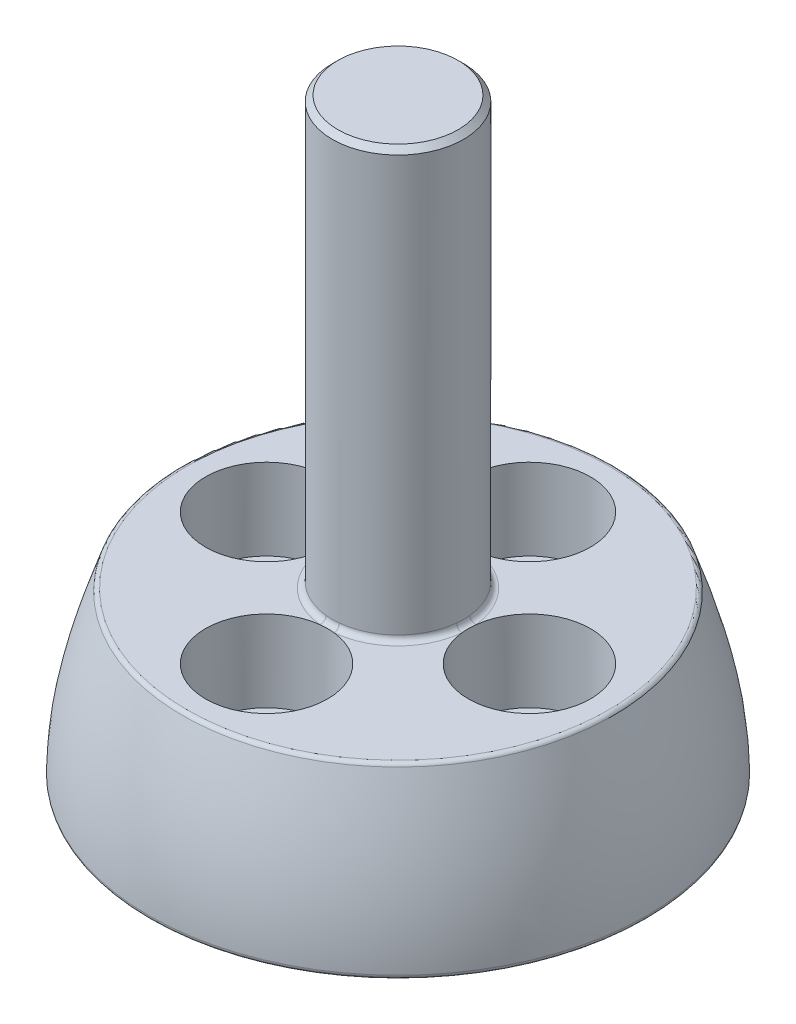
SolidWorks part; units mm, degrees
material "6061 Alloy"
ref_plane "Front" through (0, 0, 0) normal (0, 0, 1) x (1, 0, 0)
ref_plane "Top" through (0, 0, 0) normal (0, 1, 0) x (1, 0, 0)
ref_plane "Right" through (0, 0, 0) normal (1, 0, 0) x (0, 0, -1)
sketch "Sketch2" plane through (0, 0, 0) normal (0, 0, 1) x (1, 0, 0)
  line L0 (0, 0) -> (0, 26.9748) construction
  line L1 (0, 0) -> (11.3538, 0)
  line L2 (0, 26.9748) -> (2.9972, 26.9748)
  line L3 (2.9972, 26.9748) -> (2.9972, 7.493)
  line L4 (2.9972, 7.493) -> (9.779, 7.493)
  line L5 (0, 0) -> (0, 26.9748)
  spline S0 degree 3 poles (11.3538, 0) (11.3538, 2.6216) (10.6334, 5.0231) (9.779, 7.493) knots 0 0 0 0 1 1 1 1
  dimension "D1" = 11.3538
  dimension "D2" = 26.9748
  dimension "D3" = 7.493
  dimension "D4" = 2.9972
  dimension "D5" = 9.779
revolve "Revolve1" add sketch "Sketch2" angle 360 about L0
hole_wizard "CBORE for M3 SHCS1" positions "Sketch5" profile "Sketch4" counterbore size "M3" standard "ANSI Metric" end condition up to next
sketch "Sketch5" plane through (0, 7.493, 0) normal (0, 1, 0) x (1, 0, 0)
  circle A0 centre (0, 0) radius 6
  point P5 (0, 6)
  point P7 (6, 0)
  point P9 (0, -6)
  point P11 (-6, 0)
  dimension "D1" = 12
sketch "Sketch4" plane through (0, 7.493, -6) normal (1, 0, 0) x (0, 0, 1)
  line L0 (0, 0) -> (0, 7.493)
  line L1 (0, 7.493) -> (1.6, 7.493)
  line L3 (1.6, 7.493) -> (1.6, 3.71)
  line L4 (1.6, 3.71) -> (2.785, 3.71)
  line L5 (2.785, 3.71) -> (2.785, 0)
  line L7 (2.785, 0) -> (0, 0)
  line L11 (0, -6.35) -> (0, 107.95) construction
  dimension "Thru Hole Dia." = 3.2
  dimension "Thru Hole Depth" = 7.493
  dimension "C'Bore Dia." = 5.57
  dimension "C'Bore Depth" = 3.71
sketch "Sketch6" plane through (0, 0, 0) normal (0, -1, 0) x (1, 0, 0)
  circle A0 centre (0, 0) radius 2
  dimension "D1" = 4
extrude "Cut-Extrude1" cut sketch "Sketch6" against normal blind 6.85
fillet "Fillet1" radius 0.254 1 edges at (0, 7.493, -2.9972)
chamfer "Chamfer1" distance 0.254 angle 45 1 edges at (0, 26.9748, -2.9972)
fillet "Fillet2" radius 0.2032 2 edges at (0, 0, -11.3538) (0, 7.493, -9.779)
